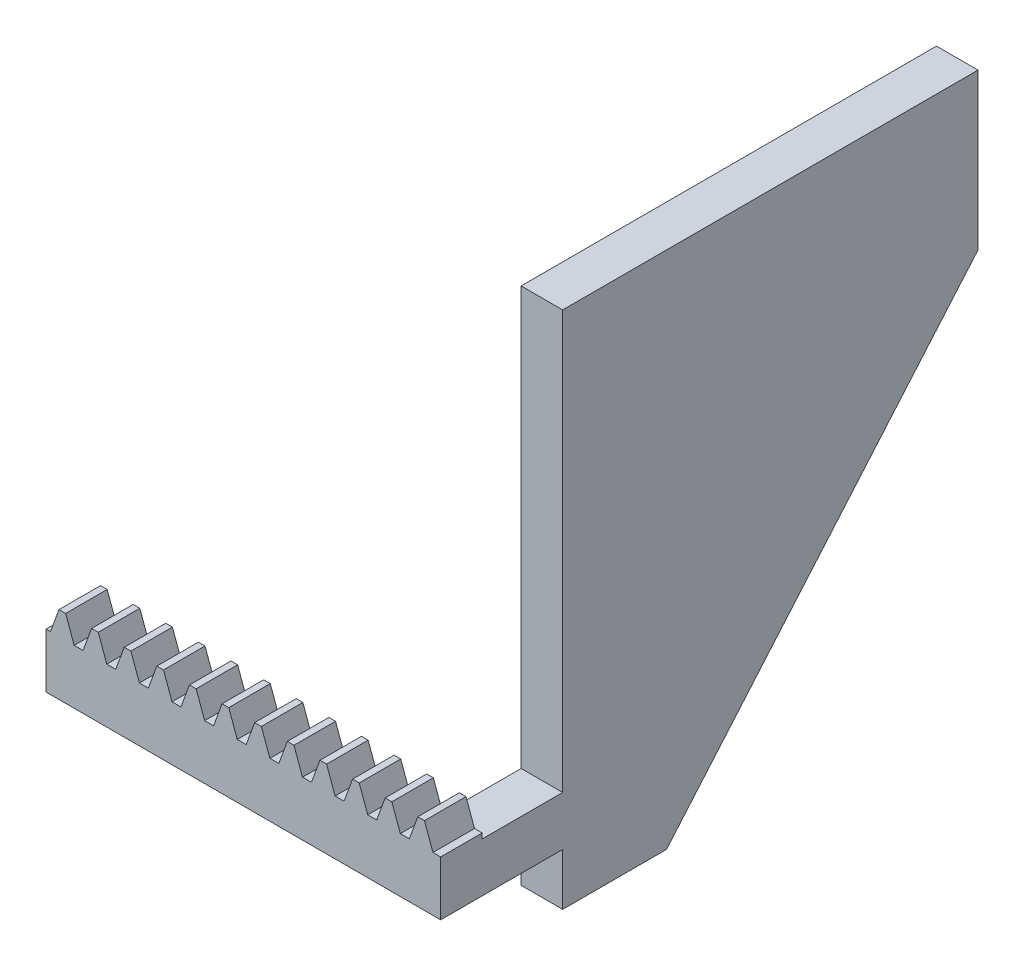
SolidWorks part; units mm, degrees
extrude "Blank" add sketch "BlankSke" against normal blind 8
sketch "BlankSke" plane through (0, 0, 0) normal (0, 0, 1) x (1, 0, 0)
  line L1 (0, 0) -> (120, 0)
  line L2 (0, 0) -> (0, 16)
  line L3 (0, 16) -> (120, 16)
  line L4 (120, 0) -> (120, 16)
  dimension "Length" = 120
  dimension "Blank_height" = 16
ref_plane "Plane1" through (0, 0, 0) normal (0, 0, 1) x (1, 0, 0)
ref_plane "Plane2" through (0, 0, 0) normal (0, 1, 0) x (1, 0, 0)
ref_plane "Plane3" through (0, 0, 0) normal (1, 0, 0) x (0, 0, -1)
sketch "HoldingSke" plane through (0, 0, 0) normal (0, 1, 0) x (1, 0, 0)
  line L0 (0, 0) -> (0.0696, 0.4951)
  line L1 (-15, 0) -> (100, 0) construction
  line L2 (0, 0) -> (-2.1039, 2.3779)
  line L3 (0, 0) -> (-11.863, 4.5341)
  line L4 (0, 0) -> (8.0624, 3.0949)
  line L5 (0, 0) -> (-23.7986, -8.8762)
  line L6 (0, 0) -> (-10.5278, -7.1032)
  line L9 (-71.009, 38.7566) -> (41.7541, 79.799)
  line L10 (-76.2, 4.3779) -> (-62.2, 4.3779)
  line L11 (0, 0) -> (-8, 0)
  line L12 (-76.2, 101.6) -> (-76.133, 101.6)
  line L13 (24.9733, 27.94) -> (52.9518, 28.4284)
  line L14 (24.9733, 27.94) -> (24.9743, 27.94)
  line L15 (24.9733, 27.94) -> (100.4006, 29.5858)
  circle A0 centre (0, 0) radius 19.05
  circle A1 centre (0, 0) radius 7
  circle A2 centre (0, 0) radius 12.7
  dimension "MPH" = 14
  dimension "Diameter" = 38.1
  dimension "Num_teeth" = 21
  dimension "Pitch" = 0.5
  dimension "Show_teeth" = 998
  dimension "Thickness" = 12.7
  dimension "Ap" = 20
  dimension "Pitch_height" = 14
  dimension "Width" = 8
  dimension "Backlash" = 0.067
  dimension "Addendum_fac" = 1
  dimension "Dedendum_fac" = 1.25
  dimension "Clearance_fac" = 0.25
  dimension "Dedendum_add" = 0.001
  dimension "Length" = 120
  dimension "Module" = 2
sketch "TooCutSkeIll" plane through (0, 0, 0) normal (0, 0, 1) x (1, 0, 0)
  line L0 (-2.4806, 15.9474) -> (-0.9819, 11.8296)
  line L1 (-0.5111, 11.5) -> (0.5111, 11.5)
  line L2 (0.9819, 11.8296) -> (2.4806, 15.9474)
  line L3 (120, 16) -> (0, 16) construction
  line L4 (0, 0) -> (0, 64.897) construction
  line L5 (-13.208, 14) -> (12.954, 14) construction
  line L6 (0, 0) -> (120, 0) construction
  line L7 (1.7718, 14) -> (1.7718, 48.7463) construction
  line L8 (-1.7718, 14) -> (-1.7718, 48.7463) construction
  line L9 (2.5558, 16) -> (2.5558, 16.0254)
  line L10 (-2.5558, 16) -> (-2.5558, 16.0254)
  line L11 (-2.5558, 16.0254) -> (2.5558, 16.0254)
  arc A0 (0.5111, 11.5) -> (0.9819, 11.8296) centre (0.5111, 12.001) ccw
  arc A1 (-0.9819, 11.8296) -> (-0.5111, 11.5) centre (-0.5111, 12.001) ccw
  arc A2 (2.5558, 16) -> (2.4806, 15.9474) centre (2.5558, 15.92) ccw
  arc A3 (-2.4806, 15.9474) -> (-2.5558, 16) centre (-2.5558, 15.92) ccw
  dimension "Pitch_height" = 14
  dimension "Addendum_plus" = 2.0254
  dimension "Pressure_angle" = 20
  dimension "Gap_width" = 3.5436
  dimension "Dedendum" = 2.5
extrude "ToothCutIll" [suppressed] cut sketch "TooCutSkeIll" against normal through all
sketch "TooCutSkeSim" plane through (0, 0, 0) normal (0, 0, 1) x (1, 0, 0)
  line L0 (0.8619, 11.5) -> (-0.8619, 11.5)
  line L1 (2.509, 16.0254) -> (0.8619, 11.5)
  line L2 (0, 17.4625) -> (0, 53.467) construction
  line L3 (2.509, 16.0254) -> (-2.509, 16.0254)
  line L6 (-2.509, 16.0254) -> (-0.8619, 11.5)
  line L9 (-1.7718, 14) -> (1.7718, 14) construction
  line L10 (0, 0) -> (120, 0) construction
  line L11 (1.7718, 14) -> (1.7718, 53.467) construction
  line L12 (-1.7718, 14) -> (-1.7718, 53.467) construction
  dimension "Pitch_height" = 14
  dimension "Addendum_plus" = 2.0254
  dimension "Pressure_angle" = 20
  dimension "Gap_width" = 3.5436
  dimension "Dedendum" = 2.5
extrude "ToothCutSim" cut sketch "TooCutSkeSim" against normal through all
pattern_linear "TeethCuts" count 20 spacing 6.2832 along (1, 0, 0) of "ToothCutIll", "ToothCutSim"
sketch "Sketch1" plane through (120, 0, 0) normal (1, 0, 0) x (0, 0, -1)
  line L0 (0, 1) -> (8, 1)
  line L1 (0, 0) -> (0, 11.5) construction
  line L2 (8, 0) -> (8, 11.5) construction
  line L3 (8, 1) -> (8, 0)
  line L4 (8, 0) -> (0, 0)
  line L5 (0, 0) -> (0, 1)
  dimension "D1" = 1
extrude "Cut-Extrude1" cut sketch "Sketch1" against normal through all
sketch "Sketch2" plane through (120, 0, 0) normal (1, 0, 0) x (0, 0, -1)
  line L0 (8, 1) -> (23.5, 1)
  line L1 (23.5, 1) -> (23.5, -9)
  line L3 (103.5, 61) -> (103.5, 91)
  line L5 (23.5, 91) -> (23.5, 10.5)
  line L6 (23.5, 10.5) -> (8, 10.5)
  line L7 (8, 1) -> (8, 11.5) construction
  line L8 (8, 10.5) -> (8, 1)
  line L9 (23.5, -9) -> (43.5, -9)
  line L10 (43.5, -9) -> (103.5, 61)
  line L13 (23.5, 91) -> (103.5, 91)
  dimension "D1" = 9.5
  dimension "D2" = 20
  dimension "D3" = 30
  dimension "D4" = 100
  dimension "D5" = 10
  dimension "D6" = 15.5
  dimension "D7" = 80
extrude "Boss-Extrude2" add sketch "Sketch2" against normal blind 8
sketch "Sketch3" plane through (0, 0, 0) normal (0, 0, 1) x (1, 0, 0)
  line L0 (0, 1) -> (0, 11.5)
  line L1 (0, 11.5) -> (0, 1) construction
  line L2 (0.8619, 11.5) -> (2.4997, 16)
  line L3 (2.4997, 16) -> (3.7834, 16)
  line L4 (3.7834, 16) -> (5.4213, 11.5)
  line L6 (5.4213, 11.5) -> (7.1451, 11.5) construction
  line L8 (0, 1) -> (120, 1) construction
  line L9 (6.1613, 1) -> (0, 1)
  line L10 (5.4213, 11.5) -> (7.1451, 11.5)
  line L11 (7.1451, 11.5) -> (8.7829, 16)
  line L12 (8.7829, 16) -> (10.0666, 16)
  line L13 (10.0666, 16) -> (11.7045, 11.5)
  line L14 (11.7045, 11.5) -> (13.4282, 11.5)
  line L15 (13.4282, 11.5) -> (15.0661, 16)
  line L16 (15.0661, 16) -> (15.708, 16)
  line L17 (16.3498, 16) -> (15.0661, 16) construction
  line L19 (0, 1) -> (112, 1) construction
  line L20 (15.708, 1) -> (6.1613, 1)
  line L21 (15.708, 16) -> (16.3498, 16)
  line L22 (16.3498, 16) -> (17.9877, 11.5)
  line L23 (17.9877, 11.5) -> (19.7114, 11.5)
  line L25 (19.7114, 11.5) -> (21.3493, 16)
  line L26 (17.9877, 1) -> (15.708, 1)
  line L27 (21.3493, 16) -> (22.633, 16)
  line L28 (22.633, 16) -> (24.2709, 11.5)
  line L29 (24.2709, 11.5) -> (25.9946, 11.5)
  line L30 (25.9946, 11.5) -> (27.6325, 16)
  line L31 (27.6325, 16) -> (28.9162, 16)
  line L32 (28.9162, 16) -> (30.5541, 11.5)
  line L33 (30.5541, 11.5) -> (32.2778, 11.5)
  line L34 (32.2778, 11.5) -> (33.9157, 16)
  line L35 (33.9157, 16) -> (35.1994, 16)
  line L36 (35.1994, 16) -> (36.8372, 11.5)
  line L37 (36.8372, 11.5) -> (37.6991, 11.5)
  line L38 (36.8372, 11.5) -> (38.561, 11.5) construction
  line L40 (37.6991, 1) -> (17.9877, 1)
  line L41 (37.6991, 11.5) -> (38.561, 11.5)
  line L42 (38.561, 11.5) -> (40.1988, 16)
  line L43 (40.1988, 16) -> (41.4826, 16)
  line L44 (41.4826, 16) -> (43.1204, 11.5)
  line L45 (43.1204, 11.5) -> (43.9823, 11.5)
  line L46 (43.1204, 11.5) -> (44.8442, 11.5) construction
  line L47 (43.9823, 11.5) -> (43.9823, 1)
  line L48 (43.9823, 1) -> (37.6991, 1)
  arc A0 (0, 11.5) -> (0.8619, 11.5) centre (0.4309, 11.5) cw
extrude "Cut-Extrude2" cut sketch "Sketch3" against normal through all
equation "' \"Module@HoldingSke\" = 6.35"
equation "' \"Num_teeth@HoldingSke\" = 12"
equation "' \"Ap@HoldingSke\" =  20"
equation "' \"Ap@HoldingSke\" = 20"
equation "' \"Width@HoldingSke\" = 0.25 * 25.4"
equation "' \"Show_teeth@HoldingSke\" = 500"
equation "' \"Backlash@HoldingSke\" = 0.009 * 25.4"
equation "' \"Addendum_fac@HoldingSke\" = 1.0"
equation "' \"Dedendum_fac@HoldingSke\" = 1.25"
equation "' \"Dedendum_add@HoldingSke\" = 0.00005 * 25.4"
equation "' \"Clearance_fac@HoldingSke\" = 0.25"
equation "' \"Pitch_height@HoldingSke\" = 1 * 25.4"
equation "' \"Length@HoldingSke\" = 4.71 * 25.4"
equation "\"Pitch@HoldingSke\" = 1 / \"Module@HoldingSke\""
equation "\"MPH@HoldingSke\" = \"Dedendum_fac@HoldingSke\" / \"Pitch@HoldingSke\" + 2 * \"Dedendum_add@HoldingSke\" + 0.002 * 25.4"
equation "\"MPH@HoldingSke\" = ((sgn( \"MPH@HoldingSke\" - \"Pitch_height@HoldingSke\")+1)*( \"MPH@HoldingSke\" - \"Pitch_height@HoldingSke\"))/2 + \"Pitch_height@HoldingSke\""
equation "\"Blank_height@BlankSke\" = \"Pitch_height@HoldingSke\" + \"Addendum_fac@HoldingSke\"  / \"Pitch@HoldingSke\" "
equation "\"Length@BlankSke\" =  \"Length@HoldingSke\""
equation "\"Face_width@Blank\" = \"Width@HoldingSke\""
equation "\"Pressure_angle@TooCutSkeIll\" = \"Ap@HoldingSke\""
equation "\"Addendum_plus@TooCutSkeIll\" =  \"Addendum_fac@HoldingSke\"  / \"Pitch@HoldingSke\" + 0.001 *25.4"
equation "\"Dedendum@TooCutSkeIll\" = \"Dedendum_fac@HoldingSke\"  / \"Pitch@HoldingSke\""
equation "\"Pitch_height@TooCutSkeIll\" =  \"MPH@HoldingSke\""
equation "\"Gap_width@TooCutSkeIll\" = 3.14159265 / 2 / \"Pitch@HoldingSke\" + 6 * \"Backlash@HoldingSke\""
equation "\"Pressure_angle@TooCutSkeSim\" = \"Ap@HoldingSke\""
equation "\"Addendum_plus@TooCutSkeSim\" =  \"Addendum_fac@HoldingSke\"  / \"Pitch@HoldingSke\" + 0.001 * 25.4"
equation "\"Dedendum@TooCutSkeSim\" = \"Dedendum_fac@HoldingSke\"  / \"Pitch@HoldingSke\""
equation "\"Pitch_height@TooCutSkeSim\" =  \"MPH@HoldingSke\""
equation "\"Gap_width@TooCutSkeSim\" = 3.14159265 / 2 / \"Pitch@HoldingSke\" + 6 * \"Backlash@HoldingSke\""
equation "\"Root_fillet@TooCutSkeIll\" = \"Clearance_fac@HoldingSke\" / \"Pitch@HoldingSke\" + \"Dedendum_add@HoldingSke\""
equation "\"Break_rad@TooCutSkeIll\" = 0.02 / \"Pitch@HoldingSke\" * 2"
equation "\"Linear_pitch@TeethCuts\" = 3.14159265 / \"Pitch@HoldingSke\""
equation "\"Num_teeth@HoldingSke\" = int( ( \"Length@HoldingSke\" + 0 ) / (3.14159265 / \"Pitch@HoldingSke\")) + 0.9999  + 1"
equation " \"Num_teeth@TeethCuts\" = int( \"Show_teeth@HoldingSke\" ) + 1"
equation " \"Num_teeth@TeethCuts\" = ((sgn( \"Num_teeth@TeethCuts\" - \"Num_teeth@HoldingSke\" )-1)*( \"Num_teeth@TeethCuts\" - \"Num_teeth@HoldingSke\" ))/-2+ \"Num_teeth@HoldingSke\""
equation " \"Num_teeth@TeethCuts\" = ((sgn( \"Num_teeth@TeethCuts\" - 2.0)+1)*( \"Num_teeth@TeethCuts\" - 2.0))/2 +2.0"
